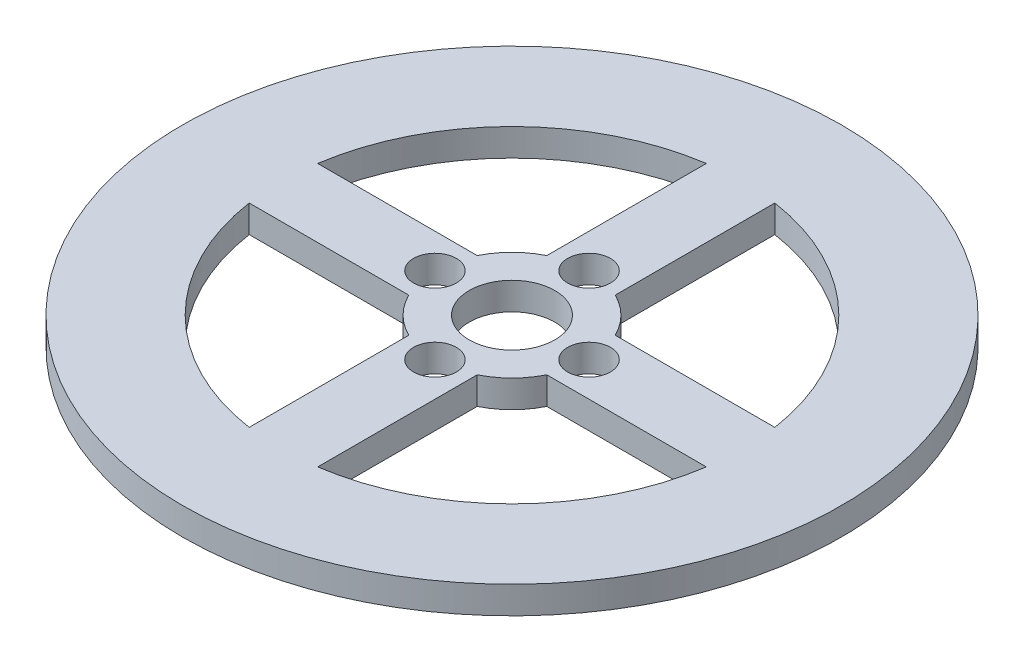
SolidWorks part; units mm, degrees
ref_plane "Alzado" through (0, 0, 0) normal (0, 0, 1) x (1, 0, 0)
ref_plane "Planta" through (0, 0, 0) normal (0, 1, 0) x (1, 0, 0)
ref_plane "Vista lateral" through (0, 0, 0) normal (1, 0, 0) x (0, 0, -1)
sketch "Croquis1" plane through (0, 0, 0) normal (0, 1, 0) x (1, 0, 0)
  circle A0 centre (0, 0) radius 19.25
  dimension "D1" = 38.5
extrude "Saliente-Extruir1" add sketch "Croquis1" along normal blind 1.6
sketch "Croquis2" plane through (0, 1.6, 0) normal (0, 1, 0) x (1, 0, 0)
  circle A0 centre (0, 0) radius 2.5
  circle A1 centre (0, 0) radius 4.5
  circle A2 centre (0, 4.5) radius 1.25
  circle A3 centre (4.5, 0) radius 1.25
  circle A4 centre (0, -4.5) radius 1.25
  circle A5 centre (-4.5, 0) radius 1.25
  dimension "D1" = 5
  dimension "D2" = 9
  dimension "D3" = 2.5
  dimension "D4" = 4
extrude "Cortar-Extruir1" cut sketch "Croquis2" against normal blind 1.6 contours A1 A5 | A1 A2 | A1 A2 | A1 A5 | A1 A4 | A1 A3 | A1 A3 | A0
sketch "Croquis3" plane through (0, 1.6, 0) normal (0, 1, 0) x (1, 0, 0)
  line L0 (-2, 13.351) -> (-2, 4.0311)
  line L1 (0, 0) -> (-1.2988, 0) construction
  line L2 (-1.2988, 0) -> (0, 0) construction
  line L3 (0, 0) -> (0, 1.0851) construction
  line L4 (2, 13.351) -> (2, 4.0311)
  line L5 (-2, -13.351) -> (-2, -4.0311)
  line L6 (2, -13.351) -> (2, -4.0311)
  line L7 (-4.0311, 2) -> (-13.351, 2)
  line L8 (-4.0311, -2) -> (-13.351, -2)
  line L9 (4.0311, -2) -> (13.351, -2)
  line L10 (4.0311, 2) -> (13.351, 2)
  circle A0 centre (0, 0) radius 13.5
  arc A1 (-4.0311, -2) -> (-2, -4.0311) centre (0, 0) ccw
  arc A6 (2, -4.0311) -> (4.0311, -2) centre (0, 0) ccw
  arc A8 (-2, 4.0311) -> (-4.0311, 2) centre (0, 0) ccw
  arc A10 (4.0311, 2) -> (2, 4.0311) centre (0, 0) ccw
  dimension "D1" = 27
  dimension "D5" = 2
extrude "Cortar-Extruir2" cut sketch "Croquis3" against normal blind 1.6 contours A8 L0 A0 L7 | A10 L10 A0 L4 | A6 L6 A0 L9 | A1 L8 A0 L5
